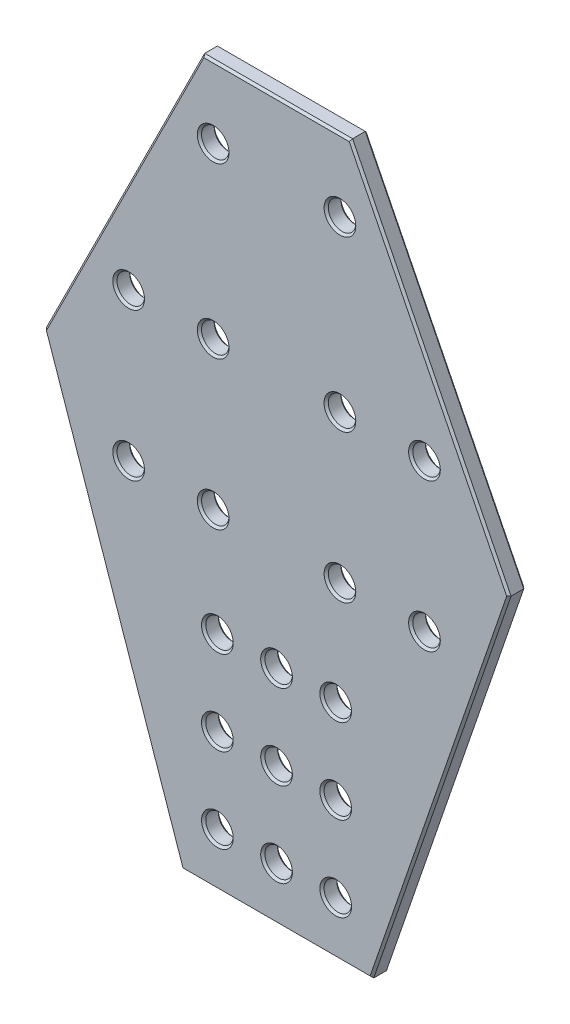
SolidWorks part; units mm, degrees
ref_plane "前视" through (0, 0, 0) normal (0, 0, 1) x (1, 0, 0)
ref_plane "上视" through (0, 0, 0) normal (0, 1, 0) x (1, 0, 0)
ref_plane "右视" through (0, 0, 0) normal (1, 0, 0) x (0, 0, -1)
sketch "草图1" plane through (0, 0, 0) normal (0, 0, 1) x (1, 0, 0)
  line L0 (-200.0754, 0) -> (200.6735, 0) construction
  line L1 (0, 0) -> (0, 111.9234) construction
  line L2 (0, 0) -> (0, -800.5573) construction
  line L3 (-70, 228) -> (70, 228)
  line L4 (-70, 228) -> (-220, -72)
  line L5 (70, 228) -> (220, -72)
  line L6 (-90, -450) -> (90, -450)
  line L7 (-220, -72) -> (-90, -450)
  line L8 (220, -72) -> (90, -450)
  line L9 (-245.8942, -140) -> (333.011, -140) construction
  line L10 (-60, -414.9282) -> (-60, 484.23) construction
  line L11 (60, 458.938) -> (60, -204.0754) construction
  line L12 (-479.9392, 160) -> (333.011, 160) construction
  line L13 (-90, -240) -> (140, -240) construction
  line L14 (-90, -320) -> (262.5772, -320) construction
  line L15 (-90, -400) -> (60, -400) construction
  line L16 (56, -431.0616) -> (56, -227) construction
  circle A0 centre (-140, 0) radius 13
  circle A1 centre (-60, 0) radius 13
  circle A2 centre (60, -140) radius 13
  circle A3 centre (140, -140) radius 13
  circle A4 centre (-140, -140) radius 13
  circle A5 centre (-60, -140) radius 13
  circle A6 centre (60, 0) radius 13
  circle A7 centre (140, 0) radius 13
  circle A8 centre (0, -400) radius 13
  circle A9 centre (0, -240) radius 13
  circle A10 centre (60, 160) radius 13
  circle A11 centre (0, -320) radius 13
  circle A12 centre (-60, 160) radius 13
  circle A13 centre (56, -240) radius 13
  circle A14 centre (56, -320) radius 13
  circle A15 centre (56, -400) radius 13
  circle A16 centre (-56, -400) radius 13
  circle A17 centre (-56, -320) radius 13
  circle A18 centre (-56, -240) radius 13
  point P8 (-220, -72)
  point P9 (220, -72)
  dimension "D10" = 26
  dimension "D17" = 68
  dimension "D18" = 56
  dimension "D11" = 26
  dimension "D1" = 140
  dimension "D2" = 228
  dimension "D3" = 300
  dimension "D4" = 220
  dimension "D5" = 678
  dimension "D6" = 180
  dimension "D7" = 140
  dimension "D8" = 60
  dimension "D9" = 60
  dimension "D12" = 100
  dimension "D13" = 80
  dimension "D14" = 80
  dimension "D15" = 80
  dimension "D16" = 80
extrude "基体-拉伸" add sketch "草图1" along normal blind 16
chamfer "倒角1" distance 2 angle 45 50 edges at (-69, -240, 0) (-69, -400, 0) (69, -320, 0) (-47, 160, 0) (13, -320, 0) (13, -400, 0) (47, 0, 0) (-127, -140, 0) (47, -140, 0) (-127, 0, 0) (-155, -261, 0) (0, -450, 0) (155, -261, 0) (145, 78, 0) (0, 228, 0) (-145, 78, 0) (-47, 0, 0) (127, -140, 0) (-47, -140, 0) (127, 0, 0) (13, -240, 0) (73, 160, 0) (69, -240, 0) (69, -400, 0) (-69, -320, 0) (-69, -240, 16) (-69, -400, 16) (69, -320, 16) (-47, 160, 16) (13, -320, 16) (13, -400, 16) (47, 0, 16) (-127, -140, 16) (47, -140, 16) (-127, 0, 16) (0, 228, 16) (145, 78, 16) (155, -261, 16) (0, -450, 16) (-155, -261, 16) (-145, 78, 16) (-47, 0, 16) (127, -140, 16) (-47, -140, 16) (127, 0, 16) (13, -240, 16) (73, 160, 16) (69, -240, 16) (69, -400, 16) (-69, -320, 16)
